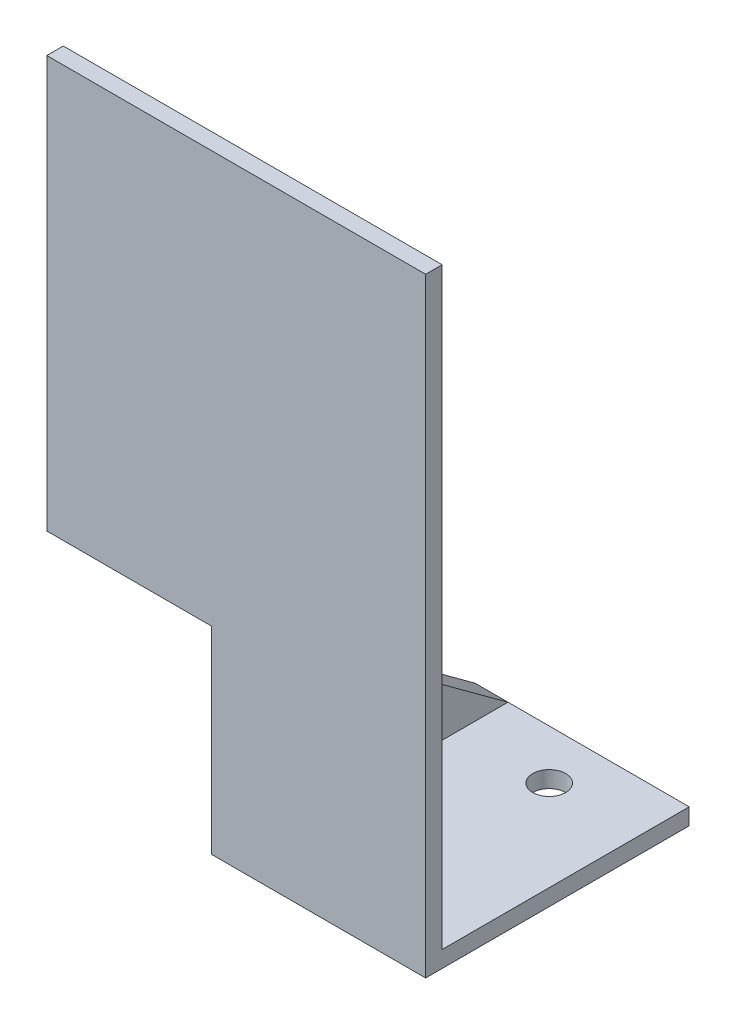
SolidWorks part; units mm, degrees
ref_plane "Front Plane" through (0, 0, 0) normal (0, 0, 1) x (1, 0, 0)
ref_plane "Top Plane" through (0, 0, 0) normal (0, 1, 0) x (1, 0, 0)
ref_plane "Right Plane" through (0, 0, 0) normal (1, 0, 0) x (0, 0, -1)
sketch "Sketch1" plane through (0, 0, 0) normal (1, 0, 0) x (0, 0, -1)
  line L5 (0, 0) -> (-101.6, 0)
  line L6 (0, 0) -> (0, 6.35)
  line L11 (0, 6.35) -> (-95.25, 6.35)
  line L12 (-101.6, 0) -> (-101.6, 6.35)
  line L14 (-101.6, 6.35) -> (-101.6, 234.95)
  line L15 (-101.6, 234.95) -> (-95.25, 234.95)
  line L16 (-95.25, 6.35) -> (-95.25, 234.95)
  point P0 (0, 0)
  dimension "D1" = 101.6
  dimension "D2" = 6.35
  dimension "D3" = 234.95
  dimension "D4" = 6.35
  dimension "D5" = 6.35
extrude "Boss-Extrude1" add sketch "Sketch1" along normal blind 146.05
sketch "Sketch2" plane through (0, 0, 101.6) normal (0, 0, 1) x (1, 0, 0)
  line L1 (0, 0) -> (63.5, 0)
  line L2 (0, 0) -> (0, 76.2)
  line L3 (0, 76.2) -> (63.5, 76.2)
  line L4 (63.5, 0) -> (63.5, 76.2)
  dimension "D1" = 76.2
  dimension "D2" = 63.5
extrude "Cut-Extrude1" cut sketch "Sketch2" against normal blind 146.05
sketch "Sketch3" plane through (63.5, 0, 0) normal (-1, 0, 0) x (0, 0, 1)
  line L0 (0, 6.35) -> (95.25, 76.2)
  line L1 (0, 6.35) -> (95.25, 6.35)
  line L2 (95.25, 6.35) -> (95.25, 76.2) construction
  line L3 (0, 6.35) -> (95.25, 6.35) construction
  line L4 (95.25, 6.35) -> (95.25, 76.2)
extrude "Boss-Extrude2" add sketch "Sketch3" against normal blind 12.7
sketch "Sketch4" plane through (0, 6.35, 0) normal (0, 1, 0) x (1, 0, 0)
  circle A0 centre (111.125, -19.05) radius 6.35
  circle A1 centre (111.125, -82.55) radius 6.35
  point P4 (0, 0)
  point P5 (0, 0)
  point P7 (0, 0)
  dimension "D1" = 12.7
  dimension "D2" = 12.7
  dimension "D3" = 34.925
  dimension "D4" = 19.05
  dimension "D5" = 19.05
extrude "Cut-Extrude2" cut sketch "Sketch4" against normal blind 12.7
